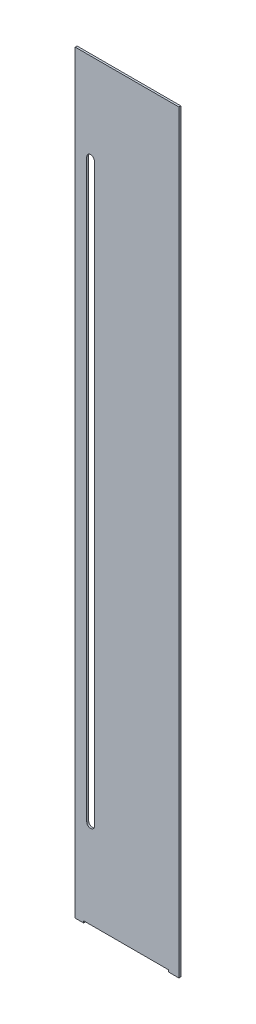
SolidWorks part; units mm, degrees
material "AISI 4340 Steel, annealed"
ref_plane "Front Plane" through (0, 0, 0) normal (0, 0, 1) x (1, 0, 0)
ref_plane "Top Plane" through (0, 0, 0) normal (0, 1, 0) x (1, 0, 0)
ref_plane "Right Plane" through (0, 0, 0) normal (1, 0, 0) x (0, 0, -1)
sketch "Sketch1" plane through (0, 0, 0) normal (0, 0, 1) x (1, 0, 0)
  line L1 (-135, 982.5) -> (135, 982.5)
  line L2 (-135, 982.5) -> (-135, -982.5)
  line L3 (-135, -982.5) -> (135, -982.5)
  line L4 (135, 982.5) -> (135, -982.5)
  line L5 (-135, 982.5) -> (135, -982.5) construction
  line L6 (-135, -982.5) -> (135, 982.5) construction
  point P0 (0, 0)
  dimension "D1" = 270
  dimension "D2" = 1965
extrude "Main plate extrude" add sketch "Sketch1" along normal blind 5
sketch "Sketch2" plane through (0, 0, 5) normal (0, 0, 1) x (1, 0, 0)
  line L0 (-135, -982.5) -> (135, -982.5) construction
  line L1 (-113, -982.5) -> (108, -982.5)
  line L2 (-113, -982.5) -> (-113, -977.5)
  line L3 (-113, -977.5) -> (108, -977.5)
  line L4 (108, -982.5) -> (108, -977.5)
  line L5 (-135, 982.5) -> (-135, -982.5) construction
  dimension "D1" = 5
  dimension "D2" = 221
  dimension "D3" = 22
extrude "Motor mount cut" cut sketch "Sketch2" against normal through all both and the other way through all
sketch "Sketch3" plane through (0, 0, 5) normal (0, 0, 1) x (1, 0, 0)
  line L0 (-95, 750) -> (-95, -750) construction
  line L1 (-85, 750) -> (-85, -750)
  line L2 (-105, 750) -> (-105, -750)
  line L3 (-135, 982.5) -> (-135, -982.5) construction
  arc A0 (-85, 750) -> (-105, 750) centre (-95, 750) ccw
  arc A1 (-105, -750) -> (-85, -750) centre (-95, -750) ccw
  point P2 (-95, 0)
  dimension "D1" = 1500
  dimension "D2" = 20
  dimension "D3" = 30
extrude "Output shaft slot" cut sketch "Sketch3" against normal through all both and the other way through all
